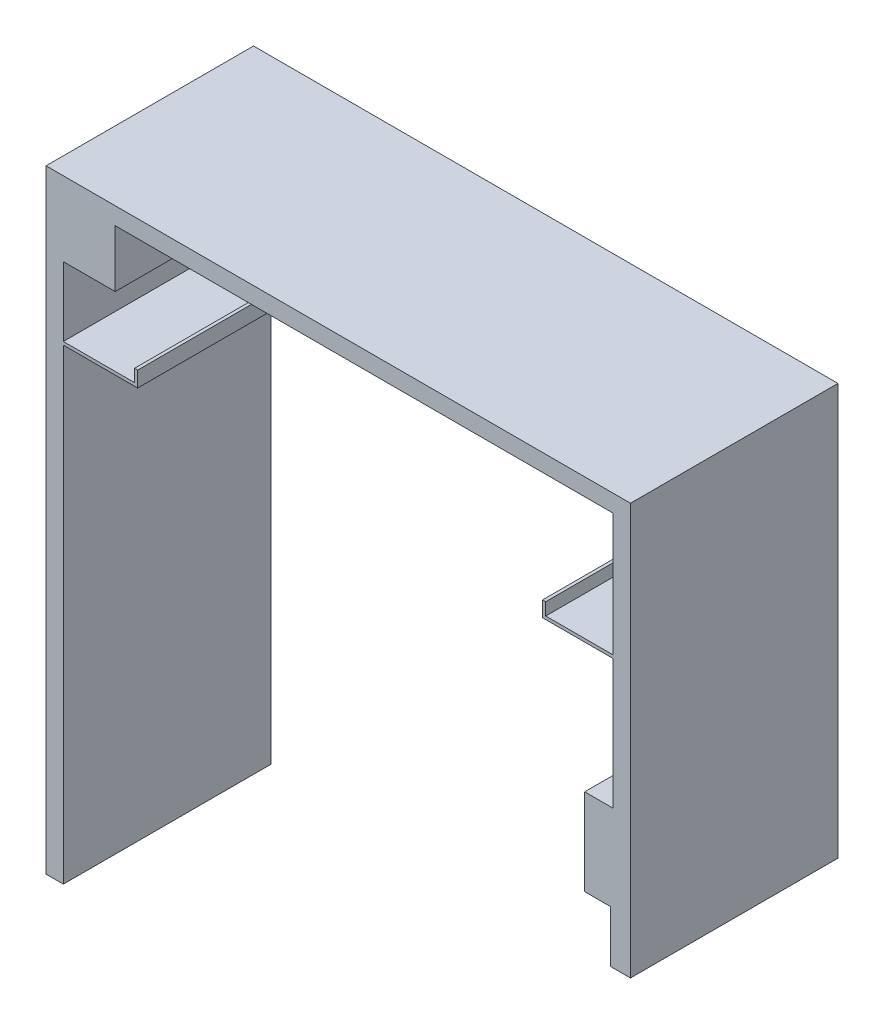
SolidWorks part; units mm, degrees
ref_plane "Plan de face" through (0, 0, 0) normal (0, 0, 1) x (1, 0, 0)
ref_plane "Plan de dessus" through (0, 0, 0) normal (0, 1, 0) x (1, 0, 0)
ref_plane "Plan de droite" through (0, 0, 0) normal (1, 0, 0) x (0, 0, -1)
sketch "Esquisse1" plane through (0, 0, 0) normal (0, 0, 1) x (1, 0, 0)
  line L0 (0, 0) -> (0, 2700)
  line L1 (0, 2700) -> (430, 2700)
  line L2 (430, 2700) -> (430, 2790)
  line L3 (430, 2790) -> (412, 2790)
  line L4 (412, 2790) -> (412, 2718)
  line L5 (412, 2718) -> (0, 2718)
  line L6 (0, 2718) -> (0, 3118)
  line L7 (0, 3118) -> (300, 3118)
  line L8 (300, 3118) -> (300, 3448)
  line L9 (300, 3448) -> (3180, 3448)
  line L10 (3180, 3448) -> (3180, 2738)
  line L11 (3180, 2738) -> (2790, 2738)
  line L12 (2790, 2738) -> (2790, 2810)
  line L13 (2790, 2810) -> (2772, 2810)
  line L14 (2772, 2810) -> (2772, 2720)
  line L15 (2772, 2720) -> (3180, 2720)
  line L16 (3180, 2720) -> (3180, 1970)
  line L17 (3180, 1970) -> (3015, 1970)
  line L18 (3015, 1970) -> (3015, 1470)
  line L19 (3015, 1470) -> (3165, 1470)
  line L20 (3165, 1470) -> (3165, 1170)
  line L21 (3165, 1170) -> (3280, 1170)
  line L22 (3280, 1170) -> (3280, 3548)
  line L23 (3280, 3548) -> (-100, 3548)
  line L24 (-100, 3548) -> (-100, 0)
  line L25 (-100, 0) -> (0, 0)
  point P21 (2684.4682, 2738)
  point P28 (3180, 2720)
  dimension "D1" = 2700
  dimension "D2" = 430
  dimension "D3" = 90
  dimension "D4" = 18
  dimension "D5" = 18
  dimension "D6" = 400
  dimension "D7" = 300
  dimension "D8" = 2880
  dimension "D9" = 100
  dimension "D10" = 100
  dimension "D11" = 100
  dimension "D12" = 18
  dimension "D13" = 18
  dimension "D14" = 90
  dimension "D15" = 300
  dimension "D16" = 710
  dimension "D17" = 750
  dimension "D18" = 165
  dimension "D19" = 500
  dimension "D20" = 150
  dimension "D21" = 330
  dimension "D22" = 390
extrude "Boss.-Extru.1" add sketch "Esquisse1" along normal blind 1200
